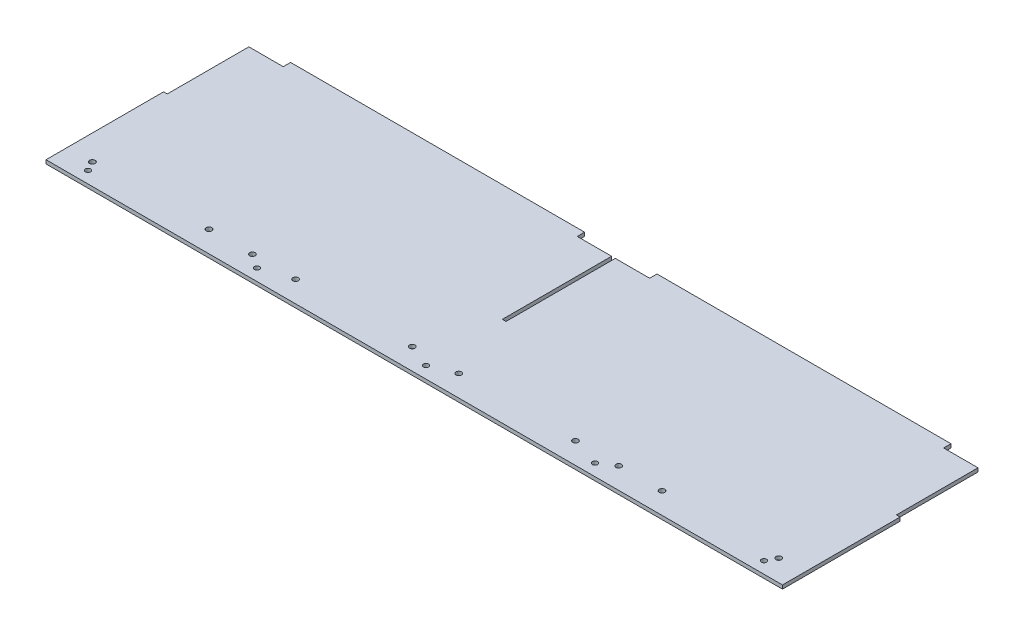
SolidWorks part; units mm, degrees
material "6061-T6 (SS)"
ref_plane "X-Y Datum" through (0, 0, 0) normal (0, 0, 1) x (1, 0, 0)
ref_plane "X-Z Datum" through (0, 0, 0) normal (0, 1, 0) x (1, 0, 0)
ref_plane "Y-Z Datum" through (0, 0, 0) normal (1, 0, 0) x (0, 0, -1)
sketch "Sketch1" plane through (0, 0, 0) normal (0, 1, 0) x (1, 0, 0)
  line L1 (0, 0) -> (636.2598, 0)
  line L2 (0, 0) -> (0, 172.0926)
  line L3 (0, 172.0926) -> (636.2598, 172.0926)
  line L4 (636.2598, 0) -> (636.2598, 172.0926)
extrude "Boss-Extrude1" add sketch "Sketch1" along normal blind 3.175 contours L3 L4 L1 L2
sketch "Sketch2" plane through (0, 0, -172.0926) normal (0, 0, -1) x (-1, 0, 0)
  line L3 (-319.7174, 3.175) -> (-316.5424, 3.175) construction
  line L4 (-319.7174, 3.175) -> (-316.5424, 3.175)
  line L5 (-319.7174, 3.175) -> (-319.7174, 0)
  line L6 (-319.7174, 0) -> (-316.5424, 0)
  line L7 (-316.5424, 3.175) -> (-316.5424, 0)
  line L9 (-319.7174, 0) -> (-316.5424, 0) construction
extrude "Cut-Extrude1" cut sketch "Sketch2" against normal blind 94.3661
sketch "Sketch3" plane through (0, 0, -172.0926) normal (0, 0, 1) x (1, 0, 0)
  line L0 (0, 0) -> (636.2598, 0) construction
  line L1 (0, 3.175) -> (3.175, 3.175)
  line L2 (0, 3.175) -> (0, 0)
  line L3 (0, 0) -> (3.175, 0)
  line L4 (3.175, 3.175) -> (3.175, 0)
  line L6 (636.2598, 3.175) -> (633.0848, 3.175)
  line L7 (636.2598, 3.175) -> (636.2598, 0)
  line L8 (636.2598, 0) -> (633.0848, 0)
  line L9 (633.0848, 3.175) -> (633.0848, 0)
extrude "Cut-Extrude5" cut sketch "Sketch3" along normal blind 70.4926
sketch "Sketch4" plane through (0, 3.175, 0) normal (0, 1, 0) x (1, 0, 0)
  line L0 (636.2598, 0) -> (636.2598, 101.6) construction
  line L1 (0, 0) -> (636.2598, 0)
  line L2 (0, 0) -> (0, 24.3942)
  line L3 (0, 24.3942) -> (636.2598, 24.3942)
  line L4 (636.2598, 0) -> (636.2598, 24.3942)
extrude "Cut-Extrude6" cut sketch "Sketch4" against normal through all
sketch "Sketch6" plane through (0, 3.175, 0) normal (0, 1, 0) x (1, 0, 0)
  line L1 (0, 24.3942) -> (636.2598, 24.3942)
  line L2 (0, 24.3942) -> (0, 0)
  line L3 (0, 0) -> (636.2598, 0)
  line L4 (636.2598, 24.3942) -> (636.2598, 0)
extrude "Boss-Extrude2" add sketch "Sketch6" against normal through all
sketch "Sketch7" plane through (0, 0, -172.0926) normal (0, 0, -1) x (-1, 0, 0)
  line L0 (-319.7174, 3.175) -> (-633.0848, 3.175) construction
  line L1 (-603.4011, 3.175) -> (-349.4011, 3.175)
  line L2 (-603.4011, 3.175) -> (-603.4011, 0)
  line L3 (-603.4011, 0) -> (-349.4011, 0)
  line L4 (-349.4011, 3.175) -> (-349.4011, 0)
  line L5 (-319.7174, 0) -> (-633.0848, 0) construction
  line L6 (-633.0848, 3.175) -> (-633.0848, 0) construction
  line L7 (-318.1299, 3.175) -> (-318.1299, 7.3465) construction
  line L9 (-32.8587, 0) -> (-286.8587, 0)
  line L10 (-286.8587, 3.175) -> (-286.8587, 0)
  line L11 (-32.8587, 3.175) -> (-286.8587, 3.175)
  line L12 (-32.8587, 3.175) -> (-32.8587, 0)
  dimension "D1" = 254
  dimension "D2" = 29.6837
extrude "Boss-Extrude3" add sketch "Sketch7" along normal blind 6.35
sketch "Sketch8" plane through (0, 3.175, 0) normal (0, 1, 0) x (1, 0, 0)
  line L0 (0, 0) -> (8.4495, 0) construction
  line L1 (0, 0) -> (0, 6.085) construction
  line L2 (0, 6.085) -> (8.4495, 6.085) construction
  line L3 (8.4495, 0) -> (8.4495, 6.085) construction
  circle A0 centre (26.1071, 10.16) radius 2.25
  circle A1 centre (172.1185, 10.16) radius 2.25
  circle A2 centre (318.1299, 10.16) radius 2.25
  circle A3 centre (464.1413, 10.16) radius 2.25
  circle A4 centre (610.1527, 10.16) radius 2.25
  point P0 (610.1527, 10.16)
  point P1 (464.1413, 10.16)
  point P2 (318.1299, 10.16)
  point P3 (172.1185, 10.16)
  point P4 (26.1071, 10.16)
extrude "Cut-Extrude7" cut sketch "Sketch8" against normal through all
sketch "Sketch9" plane through (0, 3.175, 0) normal (0, 1, 0) x (1, 0, 0)
  line L0 (19.2822, 18.3973) -> (24.0828, 18.3973) construction
  line L1 (120.0336, 18.3973) -> (124.8342, 18.3973) construction
  line L2 (157.4584, 18.3973) -> (162.259, 18.3973) construction
  line L3 (194.8832, 18.3973) -> (199.6838, 18.3973) construction
  line L4 (295.6346, 18.3973) -> (300.4352, 18.3973) construction
  line L5 (0, 0) -> (636.2598, 0) construction
  line L6 (0, 0) -> (0, 172.0926) construction
  line L7 (0, 172.0926) -> (636.2598, 172.0926) construction
  line L8 (636.2598, 0) -> (636.2598, 172.0926) construction
  line L9 (318.1299, 77.7265) -> (318.1299, 61.619) construction
  line L10 (316.5424, 77.7265) -> (319.7174, 77.7265) construction
  line L11 (340.6253, 18.3973) -> (335.8247, 18.3973) construction
  line L12 (441.3767, 18.3973) -> (436.5761, 18.3973) construction
  line L13 (478.8014, 18.3973) -> (474.0008, 18.3973) construction
  line L14 (516.2262, 18.3973) -> (511.4256, 18.3973) construction
  line L15 (616.9776, 18.3973) -> (612.177, 18.3973) construction
  circle A0 centre (21.6825, 18.3973) radius 1.5782
  circle A1 centre (122.4339, 18.3973) radius 1.9142
  circle A2 centre (159.8587, 18.3973) radius 1.0944
  circle A3 centre (197.2835, 18.3973) radius 2.3736
  circle A4 centre (298.0349, 18.3973) radius 2.21
  circle A5 centre (338.225, 18.3973) radius 2.21
  circle A6 centre (438.9764, 18.3973) radius 2.3736
  circle A7 centre (476.4011, 18.3973) radius 1.0944
  circle A8 centre (513.8259, 18.3973) radius 1.9142
  circle A9 centre (614.5773, 18.3973) radius 1.5782
hole_wizard "M4 Clearance Hole1" positions "Sketch12" profile "Sketch11" hole size "M4" standard "ANSI Metric" end condition through all
sketch "Sketch12" plane through (0, 3.175, 0) normal (0, 1, 0) x (1, 0, 0)
  line L0 (616.9776, 18.3973) -> (612.177, 18.3973) construction
  point P0 (21.6825, 18.3973)
  point P3 (122.4339, 18.3973)
  point P6 (159.8587, 18.3973)
  point P9 (197.2835, 18.3973)
  point P12 (298.0349, 18.3973)
  point P15 (338.225, 18.3973)
  point P18 (438.9764, 18.3973)
  point P21 (476.4011, 18.3973)
  point P24 (513.8259, 18.3973)
  point P27 (614.5773, 18.3973)
sketch "Sketch11" plane through (21.6825, 3.175, -18.3973) normal (1, 0, 0) x (0, 0, 1)
  line L0 (0, 0) -> (0, 3.175)
  line L1 (0, 3.175) -> (2.4, 3.175)
  line L2 (2.4, 3.175) -> (2.4, 0)
  line L5 (2.4, 0) -> (0, 0)
  line L11 (0, -6.35) -> (0, 107.95) construction
  dimension "Thru Hole Dia." = 4.8
  dimension "Thru Hole Depth" = 3.175
